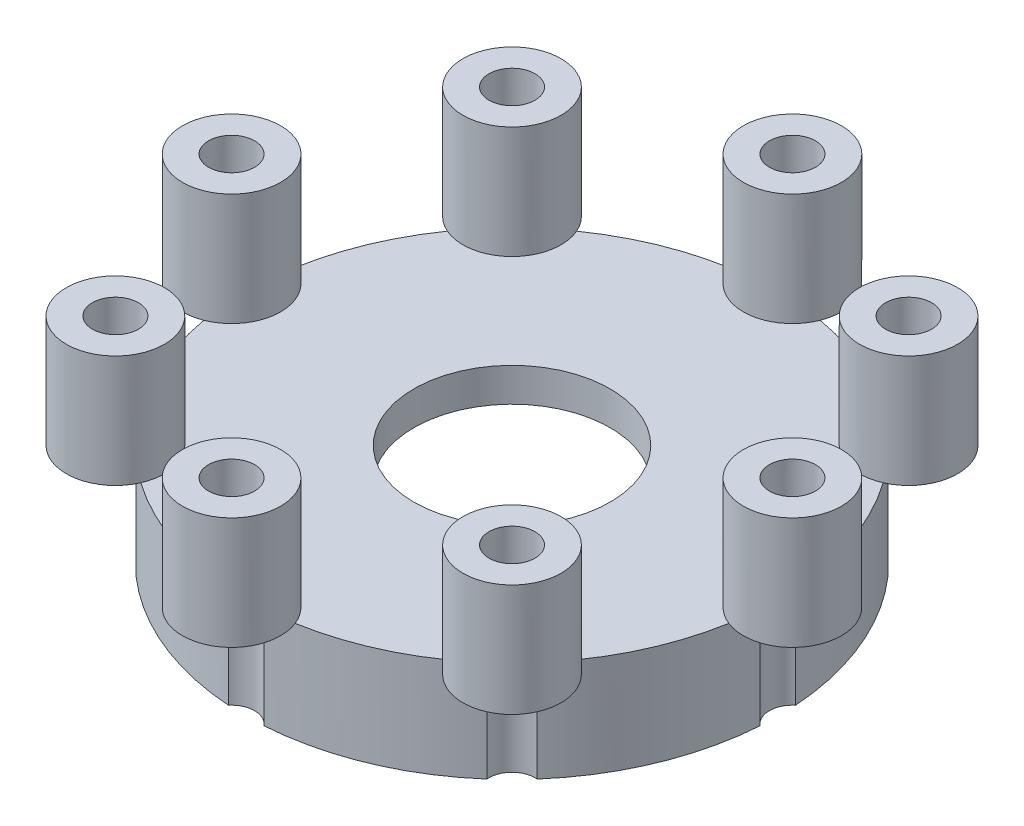
SolidWorks part; units mm, degrees
ref_plane "Front Plane" through (0, 0, 0) normal (0, 0, 1) x (1, 0, 0)
ref_plane "Top Plane" through (0, 0, 0) normal (0, 1, 0) x (1, 0, 0)
ref_plane "Right Plane" through (0, 0, 0) normal (1, 0, 0) x (0, 0, -1)
sketch "Sketch2" plane through (0, 0, 0) normal (1, 0, 0) x (0, 0, -1)
  line L0 (0, 40.5334) -> (0, -20.6352) construction
  line L1 (-47.5, 9) -> (-47.5, -9)
  line L2 (-47.5, -9) -> (-42.5, -9)
  line L3 (-42.5, -9) -> (-42.5, 3)
  line L4 (-42.5, 3) -> (-17.5, 3)
  line L5 (-17.5, 3) -> (-17.5, 9)
  line L6 (-17.5, 9) -> (-47.5, 9)
  point P9 (-47.5, 0)
  dimension "D1" = 85
  dimension "D2" = 12
  dimension "D3" = 95
  dimension "D4" = 6
  dimension "D5" = 35
revolve "Revolve1" add sketch "Sketch2" angle 360 about L0
sketch "Sketch3" plane through (0, 9, 0) normal (0, 1, 0) x (1, 0, 0)
  circle A0 centre (0, 0) radius 50 construction
  circle A1 centre (0, 50) radius 8.75
  circle A2 centre (35.3553, 35.3553) radius 8.75
  circle A3 centre (50, 0) radius 8.75
  circle A4 centre (35.3553, -35.3553) radius 8.75
  circle A5 centre (0, -50) radius 8.75
  circle A6 centre (-35.3553, -35.3553) radius 8.75
  circle A7 centre (-50, 0) radius 8.75
  circle A8 centre (-35.3553, 35.3553) radius 8.75
  point P21 (0, 0)
  dimension "D1" = 100
  dimension "D2" = 17.5
  dimension "D3" = 8
extrude "Boss-Extrude1" add sketch "Sketch3" along normal blind 20
sketch "Sketch4" plane through (0, 29, 0) normal (0, 1, 0) x (1, 0, 0)
  circle A0 centre (0, 50) radius 4.1
  circle A1 centre (35.3553, 35.3553) radius 4.1
  circle A2 centre (50, 0) radius 4.1
  circle A3 centre (35.3553, -35.3553) radius 4.1
  circle A4 centre (0, -50) radius 4.1
  circle A5 centre (-35.3553, -35.3553) radius 4.1
  circle A6 centre (-50, 0) radius 4.1
  circle A7 centre (-35.3553, 35.3553) radius 4.1
  point P19 (0, 0)
  dimension "D1" = 8.2
  dimension "D2" = 8
extrude "Cut-Extrude1" cut sketch "Sketch4" against normal through all both and the other way through all contours A0
sketch "Sketch5" plane through (0, 9, 0) normal (0, -1, 0) x (1, 0, 0)
  circle A0 centre (50, 0) radius 6.8805
  circle A1 centre (35.3553, -35.3553) radius 6.8805
  circle A2 centre (0, -50) radius 6.8805
  circle A3 centre (-35.3553, -35.3553) radius 6.8805
  circle A4 centre (-50, 0) radius 6.8805
  circle A5 centre (-35.3553, 35.3553) radius 6.8805
  circle A6 centre (0, 50) radius 6.8805
  circle A7 centre (35.3553, 35.3553) radius 6.8805
  point P19 (0, 0)
  dimension "D1" = 13.761
  dimension "D2" = 8
extrude "Cut-Extrude2" cut sketch "Sketch5" against normal blind 10 contours A7 | A5 | A4 | A3 | A2 | A1 | A0 | A6
